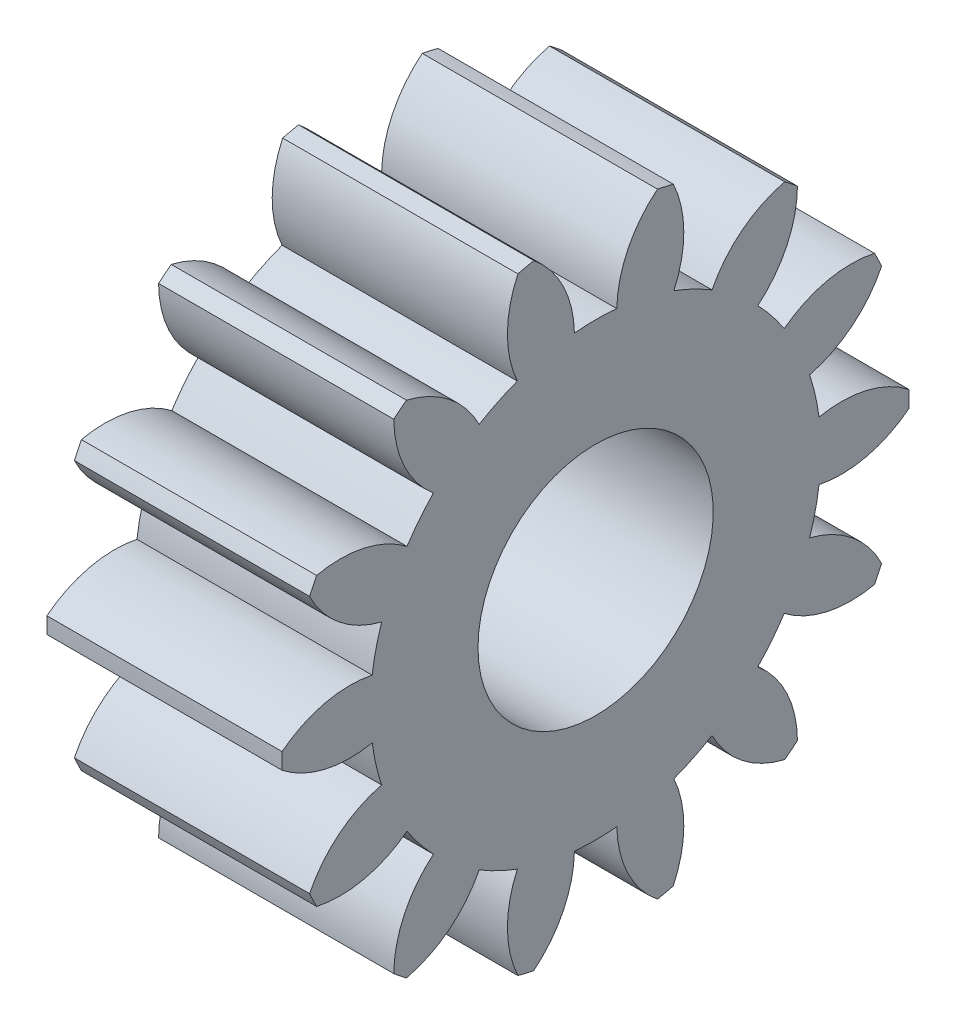
SolidWorks part; units mm, degrees
ref_plane "Plane1" through (0, 0, 0) normal (0, 0, 1) x (1, 0, 0)
ref_plane "Plane2" through (0, 0, 0) normal (0, 1, 0) x (1, 0, 0)
ref_plane "Plane3" through (0, 0, 0) normal (1, 0, 0) x (0, 0, -1)
other "Configuration Table"
sketch "HoldingSke" plane through (0, 0, 0) normal (0, 1, 0) x (1, 0, 0)
  line L0 (0, 0) -> (1.9406, -0.4838)
  line L1 (-15, 0) -> (100, 0) construction
  line L2 (0, 0) -> (-2.1039, 2.3779)
  line L3 (0, 0) -> (-11.863, 4.5341)
  line L4 (0, 0) -> (8.3795, 2.0892)
  line L5 (0, 0) -> (-46.8476, -17.4728)
  line L6 (0, 0) -> (-2.4869, -1.6779)
  line L7 (-2.1039, 2.3779) -> (8.6586, 51.2059)
  line L8 (-76.2, 54.61) -> (-75.7, 54.61)
  line L9 (-71.009, 38.7566) -> (-53.1078, 45.2721)
  line L10 (-76.2, 71.12) -> (104.1128, 71.12)
  line L11 (0, 0) -> (-3, 0)
  line L12 (-76.2, 101.6) -> (-76.181, 101.6)
  line L13 (24.9733, 27.94) -> (52.9518, 28.4284)
  line L14 (24.9733, 27.94) -> (24.9743, 27.94)
  line L15 (24.9733, 27.94) -> (100.4006, 29.5858)
  line L16 (-63.627, -0.5) -> (-12.827, -0.5)
  circle A0 centre (0, 0) radius 1.5
  circle A1 centre (0, 0) radius 2.874
  circle A2 centre (0, 0) radius 37.5
  circle A3 centre (0, 0) radius 1.5
  dimension "MHD" = 5.748
  dimension "Hub_dia" = 75
  dimension "Bore" = 3
  dimension "MBD" = 3
  dimension "Num_teeth" = 14
  dimension "Pitch" = 2
  dimension "Overall_len" = 50
  dimension "Show_teeth" = 14
  dimension "Thickness" = 3
  dimension "OAL" = 50.0001
  dimension "T_dim" = 0.5
  dimension "Ap" = 20
  dimension "H" = 19.05
  dimension "Pitch_radius" = 180.3128
  dimension "Width" = 3
  dimension "Backlash" = 0.019
  dimension "Addendum_fac" = 1
  dimension "Dedendum_fac" = 1.25
  dimension "Clearance_fac" = 0.25
  dimension "Dedendum_add" = 0.001
  dimension "Module" = 0.5
sketch "BasProSke" plane through (0, 0, 0) normal (0, 1, 0) x (1, 0, 0)
  line L0 (-10, 0) -> (60, 0) construction
  line L1 (0, 0) -> (0, 4)
  line L2 (0, 0) -> (3, 0)
  line L3 (3, 0) -> (3, 4)
  line L4 (3, 4) -> (0, 4)
  dimension "Thickness" = 3
  dimension "Diameter" = 8
revolve "Base-Revolve" add sketch "BasProSke" angle 360 about L0
sketch "TooCutSke" plane through (0, 0, 0) normal (1, 0, 0) x (0, 0, -1)
  line L1 (0, 0) -> (0, 107) construction
  line L2 (0, 0) -> (-0.4251, 3.4741) construction
  line L3 (0, 0) -> (-1.5494, 6.7886) construction
  line L4 (-0.4251, 3.4741) -> (-0.7747, 3.3943) construction
  arc A0 (0.2702, 2.8613) -> (-0.2702, 2.8613) centre (0, 0) ccw
  arc A1 (0.8149, 3.942) -> (-0.8149, 3.942) centre (0, 0) ccw
  circle A2 centre (0, 0) radius 3.5 construction
  circle A3 centre (0, 0) radius 3.2889 construction
  arc A4 (-0.2702, 2.8613) -> (-0.8149, 3.942) centre (-1.6699, 2.8334) ccw
  arc A5 (0.8149, 3.942) -> (0.2702, 2.8613) centre (1.6699, 2.8334) ccw
  dimension "Root_dia" = 5.748
  dimension "Overcut_dia" = 8.0508
  dimension "Pitch_dia" = 7
  dimension "Base_dia" = 6.5778
  dimension "Flank_rad" = 1.4
  dimension "Half_ang" = 12.857
  dimension "Half_CT" = 0.3586
extrude "ToothCut" cut sketch "TooCutSke" along normal through all
fillet "Breaks" [suppressed] radius 0.01
fillet "RootFillets" [suppressed] radius 0.126
pattern_circular "TeethCuts" count 14 every 25.714 about axis through (-10, 0, 0) along (1, 0, 0) of "ToothCut", "RootFillets", "Breaks"
sketch "HubNeaOneSke" plane through (0, 0, 0) normal (-1, 0, 0) x (0, 0, 1)
  circle A0 centre (0, 0) radius 2.874
  dimension "Diameter" = 5.748
extrude "HubNearOne" [suppressed] add sketch "HubNeaOneSke" along normal blind 47.0001
sketch "HubNeaBotSke" plane through (0, 0, 0) normal (-1, 0, 0) x (0, 0, 1)
  circle A0 centre (0, 0) radius 2.874
  dimension "Diameter" = 5.748
extrude "HubNearBoth" [suppressed] add sketch "HubNeaBotSke" along normal blind 23.5
ref_plane "FarPln" through (3, 0, 0) normal (1, 0, 0) x (0, 0, -1)
sketch "HubFarSke" plane through (3, 0, 0) normal (1, 0, 0) x (0, 0, -1)
  circle A0 centre (0, 0) radius 2.874
  dimension "Diameter" = 5.748
extrude "HubFar" [suppressed] add sketch "HubFarSke" along normal blind 23.5
sketch "BorSke" plane through (0, 0, 0) normal (1, 0, 0) x (0, 0, -1)
  circle A0 centre (0, 0) radius 1.5
  dimension "Diameter" = 3
extrude "Bore" cut sketch "BorSke" along normal mid plane 100.0001
sketch "KeySke" plane through (0, 0, 0) normal (1, 0, 0) x (0, 0, -1)
  line L0 (-0.6, 0) -> (-0.6, 2)
  line L1 (-0.6, 2) -> (0.6, 2)
  line L2 (0.6, 2) -> (0.6, 0)
  line L3 (0, 0) -> (0, 34) construction
  line L4 (-0.6, 0) -> (0.6, 0)
  dimension "Offset" = 2
  dimension "Width" = 1.2
extrude "Keyway" [suppressed] cut sketch "KeySke" along normal mid plane 100.0001
pattern_circular "Keyway2" [suppressed] count 2 every 90 about axis through (-10, 0, 0) along (1, 0, 0)
equation "' \"Module@HoldingSke\" = 6.35"
equation "' \"Num_teeth@HoldingSke\" = 12"
equation "' \"Ap@HoldingSke\" =  20"
equation "' \"Ap@HoldingSke\" = 20"
equation "' \"Width@HoldingSke\" = 0.5 * 25.4"
equation "' \"Hub_dia@HoldingSke\"= 1 * 25.4"
equation "' \"Hub_dia@HoldingSke\" = 1 * 25.4"
equation "' \"Overall_len@HoldingSke\" = 1.0 * 25.4"
equation "' \"Bore@HoldingSke\" = 0.75 * 25.4"
equation "' \"T_dim@HoldingSke\" = 0.1 * 25.4"
equation "' \"Width@KeySke\" = 0.25 * 25.4"
equation "' \"Show_teeth@HoldingSke\" = 13"
equation "' \"Backlash@HoldingSke\" = 0.009 * 25.4"
equation "' \"Addendum_fac@HoldingSke\" = 1.0"
equation "' \"Dedendum_fac@HoldingSke\" = 1.25"
equation "' \"Dedendum_add@HoldingSke\" = 0.00005 * 25.4"
equation "' \"Clearance_fac@HoldingSke\" = 0.25"
equation "\"Pitch@HoldingSke\" = 1 / \"Module@HoldingSke\""
equation "\"Overcut_dia@TooCutSke\" = (\"Num_teeth@HoldingSke\" + 2 * \"Addendum_fac@HoldingSke\") / \"Pitch@HoldingSke\" + 0.002 * 25.4"
equation "\"Pitch_dia@TooCutSke\" = \"Num_teeth@HoldingSke\" / \"Pitch@HoldingSke\""
equation "\"Base_dia@TooCutSke\" = \"Num_teeth@HoldingSke\" / \"Pitch@HoldingSke\" * cos((\"Ap@HoldingSke\"  * 3.14159265 / 180))"
equation "\"Root_dia@TooCutSke\" = (\"Num_teeth@HoldingSke\" + 2) / \"Pitch@HoldingSke\" - 2 * (\"Addendum_fac@HoldingSke\" + \"Dedendum_fac@HoldingSke\") / \"Pitch@HoldingSke\" - \"Dedendum_add@HoldingSke\" * 2"
equation "\"Half_ang@TooCutSke\" = 180 / \"Num_teeth@HoldingSke\""
equation "\"Half_CT@TooCutSke\" = \"Num_teeth@HoldingSke\" / \"Pitch@HoldingSke\" * sin((3.14159265 / 2 / \"Num_teeth@HoldingSke\")) / 2 - 7 * \"Backlash@HoldingSke\" / 4"
equation "\"Flank_rad@TooCutSke\" = \"Num_teeth@HoldingSke\" / \"Pitch@HoldingSke\" / 5"
equation "\"Radius@RootFillets\" = \"Clearance_fac@HoldingSke\" / \"Pitch@HoldingSke\" + \"Dedendum_add@HoldingSke\""
equation "\"Break_rad@Breaks\" = 0.02 / \"Pitch@HoldingSke\""
equation "\"Thickness@HoldingSke\" = \"Width@HoldingSke\""
equation "\"OAL@HoldingSke\" = \"Thickness@HoldingSke\""
equation "\"MHD@HoldingSke\" = (\"Num_teeth@HoldingSke\" + 2) / \"Pitch@HoldingSke\" - 2 * (\"Addendum_fac@HoldingSke\" + \"Dedendum_fac@HoldingSke\")  / \"Pitch@HoldingSke\" - \"Dedendum_add@HoldingSke\" * 2"
equation "\"MBD@HoldingSke\" = (\"Num_teeth@HoldingSke\" + 2) / \"Pitch@HoldingSke\" - 2 * (\"Addendum_fac@HoldingSke\" + \"Dedendum_fac@HoldingSke\")  / \"Pitch@HoldingSke\" - \"Dedendum_add@HoldingSke\" * 2 - 0.002 * 25.4"
equation "\"MHD@HoldingSke\" = ((sgn( \"MHD@HoldingSke\" - \"Hub_dia@HoldingSke\" )-1)*( \"MHD@HoldingSke\" - \"Hub_dia@HoldingSke\" ))/-2+ \"Hub_dia@HoldingSke\""
equation "\"MBD@HoldingSke\" = ((sgn( \"MBD@HoldingSke\" - \"Bore@HoldingSke\" )-1)*( \"MBD@HoldingSke\" - \"Bore@HoldingSke\" ))/-2+ \"Bore@HoldingSke\""
equation "\"OAL@HoldingSke\" = ((sgn( \"OAL@HoldingSke\" - \"Overall_len@HoldingSke\" )+1)*( \"OAL@HoldingSke\" - \"Overall_len@HoldingSke\" ))/2 + \"Overall_len@HoldingSke\" + 0.000002 * 25.4"
equation "\"Num_teeth@TeethCuts\" = int( \"Show_teeth@HoldingSke\" ) + 1"
equation "\"Num_teeth@TeethCuts\" = ((sgn( \"Num_teeth@TeethCuts\" - \"Num_teeth@HoldingSke\" )-1)*( \"Num_teeth@TeethCuts\" - \"Num_teeth@HoldingSke\" ))/-2+ \"Num_teeth@HoldingSke\""
equation "\"Num_teeth@TeethCuts\" = ((sgn( \"Num_teeth@TeethCuts\" - 2.0)+1)*( \"Num_teeth@TeethCuts\" - 2.0))/2 +2.0"
equation "\"Angle@TeethCuts\" = 360.0 / \"Num_teeth@HoldingSke\""
equation "\"Diameter@BasProSke\" = (\"Num_teeth@HoldingSke\" + 2 * \"Addendum_fac@HoldingSke\") / \"Pitch@HoldingSke\""
equation "\"Thickness@BasProSke\"  = \"Thickness@HoldingSke\""
equation "' \"Fillet_rad@BasProSke\" =  \"Thickness@HoldingSke\" * 0.05"
equation "' \"Fillet_rad@BasProSke\" = \"Thickness@HoldingSke\" * 0.05"
equation "\"MHD@HoldingSke\" = ((sgn( \"MHD@HoldingSke\" - \"Root_dia@TooCutSke\" )-1)*( \"MHD@HoldingSke\" - \"Root_dia@TooCutSke\" ))/-2+ \"Root_dia@TooCutSke\""
equation "\"Diameter@HubNeaOneSke\" = \"MHD@HoldingSke\""
equation "\"Length@HubNearOne\" = \"OAL@HoldingSke\" - \"Thickness@BasProSke\""
equation "\"Diameter@HubNeaBotSke\" = \"MHD@HoldingSke\""
equation "\"Length@HubNearBoth\" = ( \"OAL@HoldingSke\" - \"Thickness@BasProSke\" ) / 2.0"
equation "\"Thickness@FarPln\" = \"Thickness@BasProSke\""
equation "\"Diameter@HubFarSke\" = \"MHD@HoldingSke\""
equation "\"Length@HubFar\" = ( \"OAL@HoldingSke\" - \"Thickness@BasProSke\" ) / 2.0"
equation "\"Diameter@BorSke\" = \"MBD@HoldingSke\""
equation "\"D1@Bore\" = \"OAL@HoldingSke\" * 2.0"
equation "\"D1@Keyway\" = \"OAL@HoldingSke\" * 2.0"
equation "\"Offset@KeySke\" = \"T_dim@HoldingSke\" + \"MBD@HoldingSke\" / 2.0"
